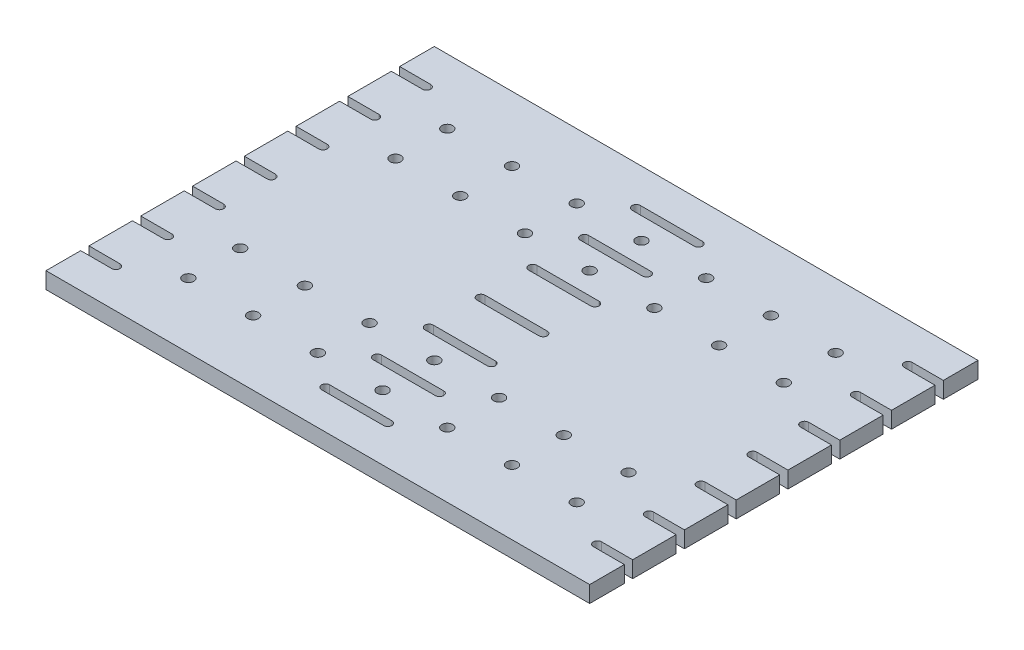
SolidWorks part; units mm, degrees
ref_plane "Front Plane" through (0, 0, 0) normal (0, 0, 1) x (1, 0, 0)
ref_plane "Top Plane" through (0, 0, 0) normal (0, 1, 0) x (1, 0, 0)
ref_plane "Right Plane" through (0, 0, 0) normal (1, 0, 0) x (0, 0, -1)
sketch "Sketch1" plane through (0, 0, 0) normal (0, 1, 0) x (1, 0, 0)
  line L1 (105, -75) -> (-105, -75)
  line L2 (105, -75) -> (105, 75)
  line L3 (105, 75) -> (-105, 75)
  line L4 (-105, -75) -> (-105, 75)
  line L5 (105, -75) -> (-105, 75) construction
  line L6 (105, 75) -> (-105, -75) construction
  point P0 (0, 0)
  dimension "D1" = 210
  dimension "D2" = 150
extrude "Boss-Extrude1" add sketch "Sketch1" along normal blind 6.35
sketch "Sketch3" plane through (0, 6.35, 0) normal (0, 1, 0) x (1, 0, 0)
  line L0 (12, 0) -> (-12, 0) construction
  line L1 (12, -1.6) -> (-12, -1.6)
  line L2 (12, 1.6) -> (-12, 1.6)
  arc A0 (12, -1.6) -> (12, 1.6) centre (12, 0) ccw
  arc A1 (-12, 1.6) -> (-12, -1.6) centre (-12, 0) ccw
  point P2 (0, 0)
  dimension "D1" = 3.2
  dimension "D2" = 24
extrude "Cut-Extrude1" cut sketch "Sketch3" against normal through all both and the other way through all
pattern_linear "LPattern1" count 4 spacing 20 along (0, 0, 1) count 4 spacing 20 along (0, 0, -1) of "Cut-Extrude1"
pattern_linear "LPattern2" count 2 spacing 105 along (1, 0, 0) count 2 spacing 105 along (-1, 0, 0) of "LPattern1", "Cut-Extrude1"
sketch "Sketch4" plane through (0, 6.35, 0) normal (0, 1, 0) x (1, 0, 0)
  circle A0 centre (0, 30) radius 2.1
  circle A1 centre (0, -30) radius 2.1
  circle A2 centre (0, 50) radius 2.1
  circle A3 centre (0, -50) radius 2.1
  dimension "D5" = 4.2
  dimension "D1" = 30
  dimension "D2" = 20
  dimension "D3" = 30
  dimension "D4" = 20
extrude "Cut-Extrude2" cut sketch "Sketch4" against normal through all both and the other way through all
pattern_linear "LPattern3" count 4 spacing 25 along (1, 0, 0) count 4 spacing 25 along (-1, 0, 0) of "Cut-Extrude2"
